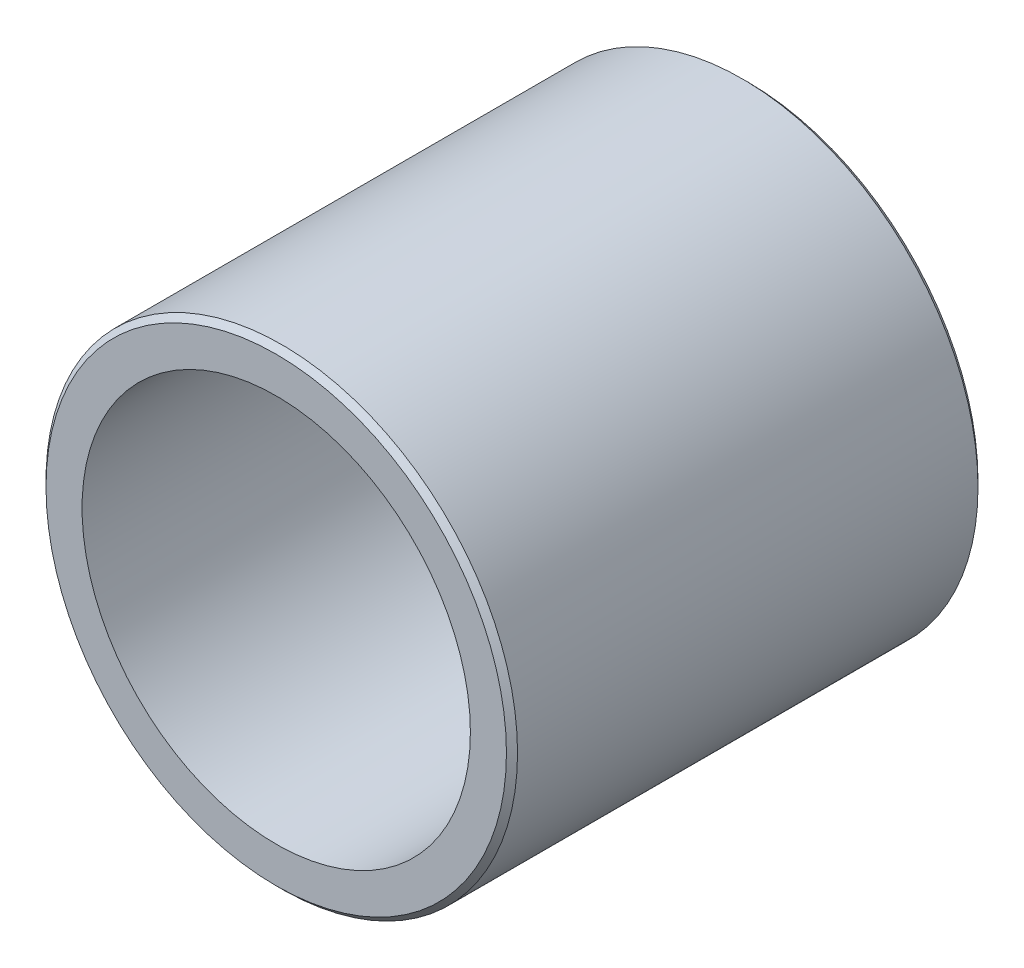
SolidWorks part; units mm, degrees
ref_plane "Front Plane" through (0, 0, 0) normal (0, 0, 1) x (1, 0, 0)
ref_plane "Top Plane" through (0, 0, 0) normal (0, 1, 0) x (1, 0, 0)
ref_plane "Right Plane" through (0, 0, 0) normal (1, 0, 0) x (0, 0, -1)
sketch "Sketch1" plane through (0, 0, 0) normal (0, 0, 1) x (1, 0, 0)
  circle A0 centre (0, 0) radius 44.45
  circle A1 centre (0, 0) radius 53.975
  dimension "D1" = 107.95
  dimension "D2" = 88.9
extrude "Boss-Extrude1" add sketch "Sketch1" along normal mid plane 107.95
chamfer "Chamfer1" distance 1.27 angle 45 2 edges at (53.975, 0, 53.975) (53.975, 0, -53.975)
